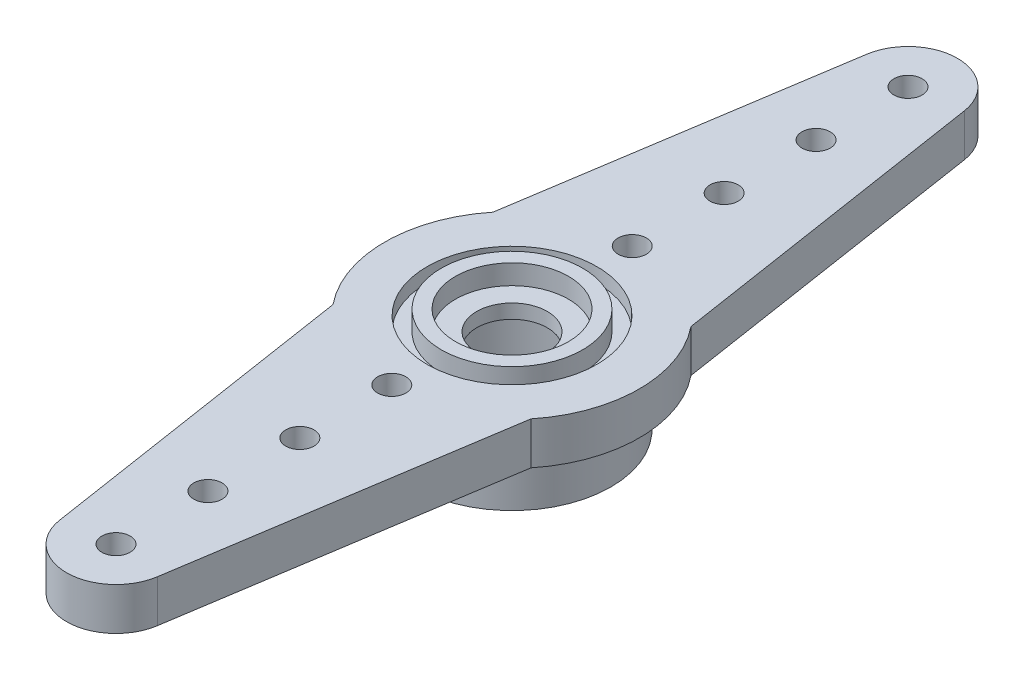
SolidWorks part; units mm, degrees
ref_plane "Front Plane" through (0, 0, 0) normal (0, 0, 1) x (1, 0, 0)
ref_plane "Top Plane" through (0, 0, 0) normal (0, 1, 0) x (1, 0, 0)
ref_plane "Right Plane" through (0, 0, 0) normal (1, 0, 0) x (0, 0, -1)
sketch "Sketch1" plane through (0, 0, 0) normal (0, 1, 0) x (1, 0, 0)
  circle A0 centre (0, 0) radius 4.5
  dimension "D1" = 9
extrude "Boss-Extrude1" add sketch "Sketch1" along normal blind 1.5
sketch "Sketch2" plane through (0, 0, 0) normal (0, 1, 0) x (1, 0, 0)
  line L0 (0, 0) -> (0, 14) construction
  line L1 (3.5, 2.8284) -> (1.7294, 14.2677)
  line L2 (-1.7294, 14.2677) -> (-3.5, 2.8284)
  line L3 (-3.5, 2.8284) -> (3.5, 2.8284)
  circle A0 centre (0, 0) radius 4.5 construction
  arc A1 (1.7294, 14.2677) -> (-1.7294, 14.2677) centre (0, 14) ccw
  dimension "D1" = 1.75
  dimension "D2" = 7
  dimension "D3" = 14
extrude "Boss-Extrude2" add sketch "Sketch2" along normal blind 1.5
hole_wizard "Ø1.0 (1) Diameter Hole1" positions "Sketch4" profile "Sketch5" hole size "Ø1.0" standard "ANSI Metric"
sketch "Sketch4" plane through (0, 1.5, 0) normal (0, 1, 0) x (1, 0, 0)
  line L0 (0, 14) -> (0, 10.75) construction
  line L1 (0, 10.75) -> (0, 7.5) construction
  line L2 (0, 7.5) -> (0, 4.25) construction
  point P0 (0, 14)
  point P2 (0, 10.75)
  point P4 (0, 7.5)
  point P17 (0, 4.25)
  point P20 (0, 3.0226)
  point P25 (0, 14)
  dimension "D1" = 3.25
sketch "Sketch5" plane through (0, 1.5, -14) normal (1, 0, 0) x (0, 0, 1)
  line L0 (0, 0) -> (0, 7.8004)
  line L1 (0, 7.8004) -> (0.5, 7.5)
  line L2 (0.5, 7.5) -> (0.5, 0)
  line L5 (0.5, 0) -> (0, 0)
  line L10 (0, 7.8004) -> (-0.5, 7.5) construction
  line L11 (0, -6.35) -> (0, 107.95) construction
  dimension "Hole Dia." = 1
  dimension "Hole Depth" = 7.5
  dimension "Drill Angle" = 118
pattern_circular "CirPattern1" count 2 over 360 about axis through (0, 0, 0) along (0, 1, 0) of "Boss-Extrude2", "Ø1.0 (1) Diameter Hole1"
sketch "Sketch6" plane through (0, 1.5, 0) normal (0, 1, 0) x (1, 0, 0)
  circle A0 centre (0, 0) radius 3
  dimension "D1" = 6
extrude "Cut-Extrude1" cut sketch "Sketch6" against normal blind 0.5
sketch "Sketch7" plane through (0, 1, 0) normal (0, 1, 0) x (1, 0, 0)
  circle A0 centre (0, 0) radius 2.5
  dimension "D1" = 5
extrude "Extrude-Thin1" add sketch "Sketch7" along normal blind 0.7 thin thin type one direction reverse wall 0.5
sketch "Sketch8" plane through (0, 1, 0) normal (0, 1, 0) x (1, 0, 0)
  circle A0 centre (0, 0) radius 1.25
  dimension "D1" = 2.5
extrude "Cut-Extrude2" cut sketch "Sketch8" against normal through all
sketch "Sketch9" plane through (0, 0, 0) normal (0, -1, 0) x (1, 0, 0)
  circle A0 centre (0, 0) radius 3.5
  dimension "D1" = 7
extrude "Boss-Extrude3" add sketch "Sketch9" along normal blind 2
sketch "Sketch10" plane through (0, -2, 0) normal (0, -1, 0) x (1, 0, 0)
  circle A0 centre (0, 0) radius 3
  dimension "D1" = 6
extrude "Cut-Extrude3" cut sketch "Sketch10" against normal offset from surface (2.5 mm away) 0.5 up to face at (0, 1, 1.25)
